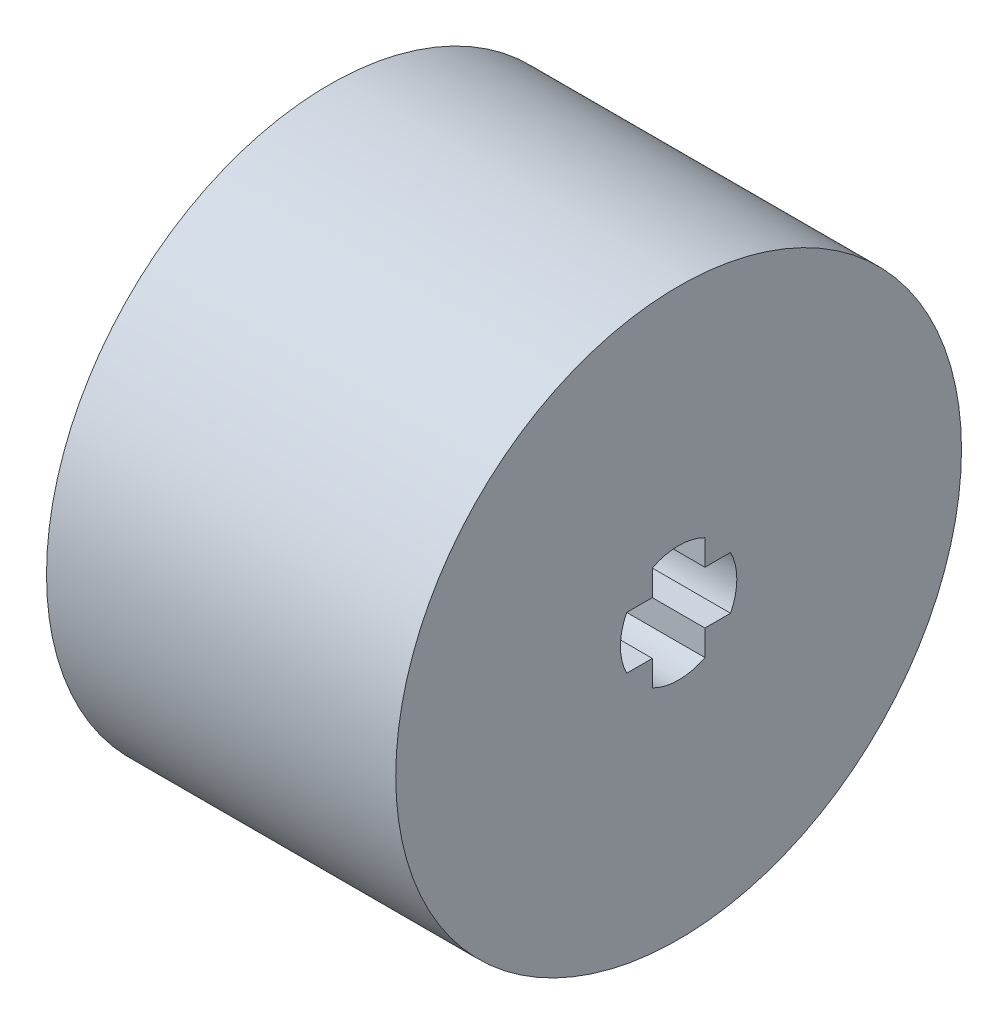
SolidWorks part; units mm, degrees
ref_plane "前视基准面" through (0, 0, 0) normal (0, 0, 1) x (1, 0, 0)
ref_plane "上视基准面" through (0, 0, 0) normal (0, 1, 0) x (1, 0, 0)
ref_plane "右视基准面" through (0, 0, 0) normal (1, 0, 0) x (0, 0, -1)
other "Configuration Table"
sketch "草图1" plane through (0, 0, 0) normal (1, 0, 0) x (0, 0, -1)
  circle A0 centre (0, 0) radius 12.15
  dimension "D1" = 24.3
extrude "凸台-拉伸1" add sketch "草图1" along normal blind 15
sketch "草图2" plane through (15, 0, 0) normal (1, 0, 0) x (0, 0, -1)
  line L3 (-2.23, 1.13) -> (-1.13, 1.13)
  line L4 (-1.13, -2.23) -> (1.13, -2.23)
  line L5 (-1.13, -2.23) -> (-1.13, 2.23)
  line L6 (-1.13, 2.23) -> (1.13, 2.23)
  line L7 (1.13, -2.23) -> (1.13, 2.23)
  line L8 (-1.13, -2.23) -> (1.13, 2.23) construction
  line L9 (-1.13, 2.23) -> (1.13, -2.23) construction
  line L10 (-2.23, -1.13) -> (2.23, -1.13)
  line L11 (-2.23, -1.13) -> (-2.23, 1.13)
  line L12 (-2.23, 1.13) -> (2.23, 1.13)
  line L13 (2.23, -1.13) -> (2.23, 1.13)
  line L14 (-2.23, -1.13) -> (2.23, 1.13) construction
  line L15 (-2.23, 1.13) -> (2.23, -1.13) construction
  line L18 (0, 3.7) -> (0, -3.7) construction
  circle A0 centre (0, 0) radius 2.5
  circle A10 centre (0, 0) radius 3.15 construction
  circle A11 centre (0, 0) radius 3.7 construction
  dimension "D1" = 7.4
  dimension "D2" = 6.3
  dimension "D3" = 5
  dimension "D5" = 1.1
extrude "切除-拉伸1" cut sketch "草图2" against normal through all contours L5 L12 L7 L6 | L11 L10 L5 L3 | L10 L5 L4 L7 | L10 L13 L12 L7 | L12 L5 L10 L7 | L6 A0 | L13 A0 | L4 A0 | L11 A0
ref_plane "基准面1" through (0, 0, 12.15) normal (0, 0, 1) x (1, 0, 0)
ref_plane "基准面2" through (0, 0, 6.35) normal (0, 0, 1) x (1, 0, 0)
sketch "草图3" plane through (0, 0, 0) normal (-1, 0, 0) x (0, 0, 1)
  circle A0 centre (0, 0) radius 7.5
  dimension "D1" = 15
extrude "切除-拉伸2" cut sketch "草图3" against normal blind 4
sketch "草图4" plane through (4, 0, 0) normal (-1, 0, 0) x (0, 0, 1)
  circle A0 centre (0, 0) radius 4
  dimension "D1" = 8
extrude "切除-拉伸3" cut sketch "草图4" against normal blind 3
